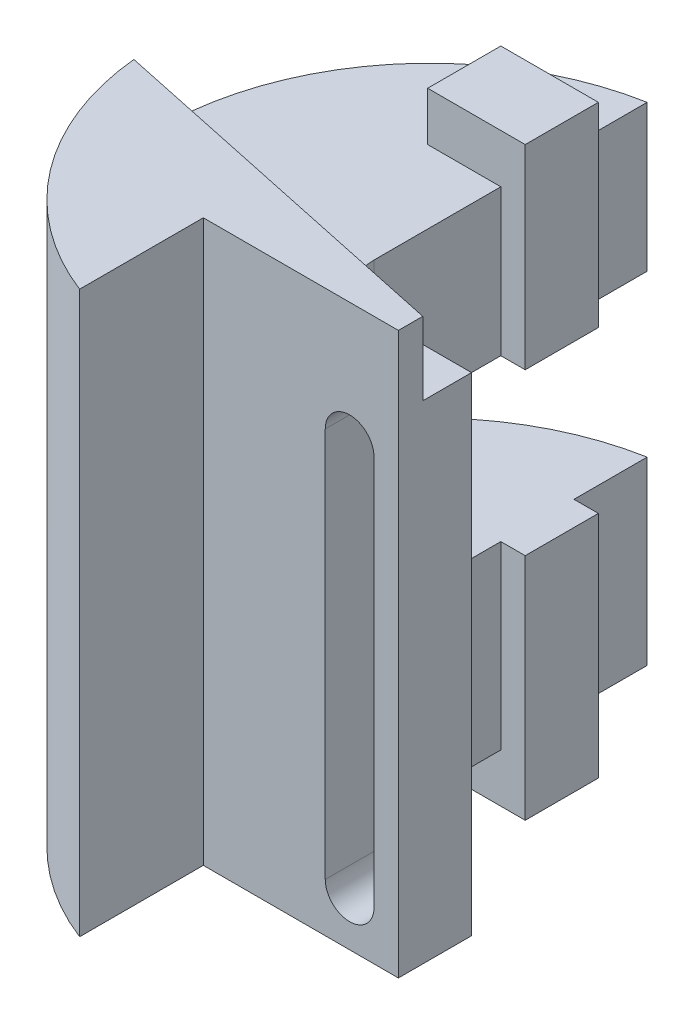
SolidWorks part; units mm, degrees
material "1060 Alloy"
ref_plane "Front Plane" through (0, 0, 0) normal (0, 0, 1) x (1, 0, 0)
ref_plane "Top Plane" through (0, 0, 0) normal (0, 1, 0) x (1, 0, 0)
ref_plane "Right Plane" through (0, 0, 0) normal (1, 0, 0) x (0, 0, -1)
sketch "Sketch1" plane through (0, 0, 0) normal (0, 1, 0) x (1, 0, 0)
  line L0 (0, 0) -> (0, -15)
  line L1 (0, -15) -> (5, -15)
  line L2 (5, -15) -> (5, -30)
  line L3 (5, -30) -> (0, -30)
  line L4 (0, -30) -> (0, -56)
  line L5 (10, -66) -> (30, -66)
  line L6 (30, -66) -> (30, -81)
  line L7 (30, -81) -> (-10, -81)
  line L8 (-10, -81) -> (-10, -106.3628)
  line L9 (10, -66) -> (10, -23.5557) construction
  arc A0 (0, -56) -> (10, -66) centre (10, -56) ccw
  arc A1 (0, 0) -> (-10, -106.3628) centre (10, -54.5917) ccw
  point P14 (-5.0133, -55.2731)
  dimension "D9" = 55.5
  dimension "D1" = 40
  dimension "D2" = 15
  dimension "D3" = 66
  dimension "D4" = 5
  dimension "D5" = 10
  dimension "D6" = 20
  dimension "D7" = 15
  dimension "D8" = 15
extrude "Boss-Extrude1" add sketch "Sketch1" along normal blind 100
sketch "Sketch2" plane through (0, 100, 0) normal (0, 1, 0) x (1, 0, 0)
  line L0 (30, -81) -> (30, -76)
  line L1 (30, -81) -> (30, -66) construction
  line L2 (30, -76) -> (-45.235, -60.0083)
  line L3 (30, -81) -> (-10, -81)
  line L4 (-10, -81) -> (-10, -106.3628)
  line L5 (10, -66) -> (10, -43.1181) construction
  line L6 (30, -66) -> (10, -66) construction
  arc A0 (0, 0) -> (-10, -106.3628) centre (10, -54.5917) ccw construction
  arc A1 (-10, -106.3628) -> (-45.235, -60.0083) centre (10, -54.5917) cw
  arc A2 (0, -56) -> (10, -66) centre (10, -56) ccw construction
  dimension "D1" = 5
  dimension "D2" = 78
extrude "Boss-Extrude2" add sketch "Sketch2" along normal blind 15
sketch "Sketch4" plane through (0, 0, 66) normal (0, 0, -1) x (-1, 0, 0)
  line L0 (-20, 90) -> (-20, 10) construction
  line L1 (-15, 90) -> (-15, 10)
  line L2 (-25, 90) -> (-25, 10)
  line L3 (-30, 100) -> (-30, 0) construction
  line L4 (-30, 0) -> (-10, 0) construction
  arc A0 (-15, 90) -> (-25, 90) centre (-20, 90) ccw
  arc A1 (-25, 10) -> (-15, 10) centre (-20, 10) ccw
  point P2 (-20, 50)
  dimension "D2" = 5
  dimension "D1" = 80
  dimension "D3" = 10
  dimension "D4" = 10
extrude "Cut-Extrude1" cut sketch "Sketch4" against normal blind 15
sketch "Sketch5" plane through (0, 100, 0) normal (0, 1, 0) x (1, 0, 0)
  line L0 (5, -15) -> (-15, -15)
  line L1 (-15, -15) -> (-15, -30)
  line L2 (-15, -30) -> (5, -30)
  line L3 (5, -30) -> (5, -15)
sketch "Sketch6" plane through (0, 0, 0) normal (0, -1, 0) x (-1, 0, 0)
  line L0 (-5, -30) -> (15, -30)
  line L1 (15, -30) -> (15, -15)
  line L2 (15, -15) -> (-5, -15)
  line L3 (-5, -15) -> (-5, -30)
extrude "Boss-Extrude3" add sketch "Sketch6" along normal blind 10
extrude "Boss-Extrude4" add sketch "Sketch5" along normal blind 10 contours L0 L1 L2 L3
sketch "Sketch7" plane through (5, 0, 0) normal (1, 0, 0) x (0, 0, -1)
  line L0 (0, 70) -> (-40, 70)
  line L1 (0, 100) -> (0, 0) construction
  line L2 (-40, 70) -> (-40, 37)
  line L3 (-40, 37) -> (0, 37)
  line L4 (0, 37) -> (0, 70)
  line L5 (-15, 100) -> (0, 100) construction
  dimension "D1" = 33
  dimension "D2" = 30
  dimension "D3" = 40
extrude "Cut-Extrude2" cut sketch "Sketch7" against normal blind 70
equation "\"A\"= 55.5"
equation "\"B\"= 66"
equation "\"C\"= 33"
equation "\"D3@Sketch1\"=\"B\""
equation "\"D9@Sketch1\"=\"A\""
equation "\"D1@Sketch7\"=\"C\""
